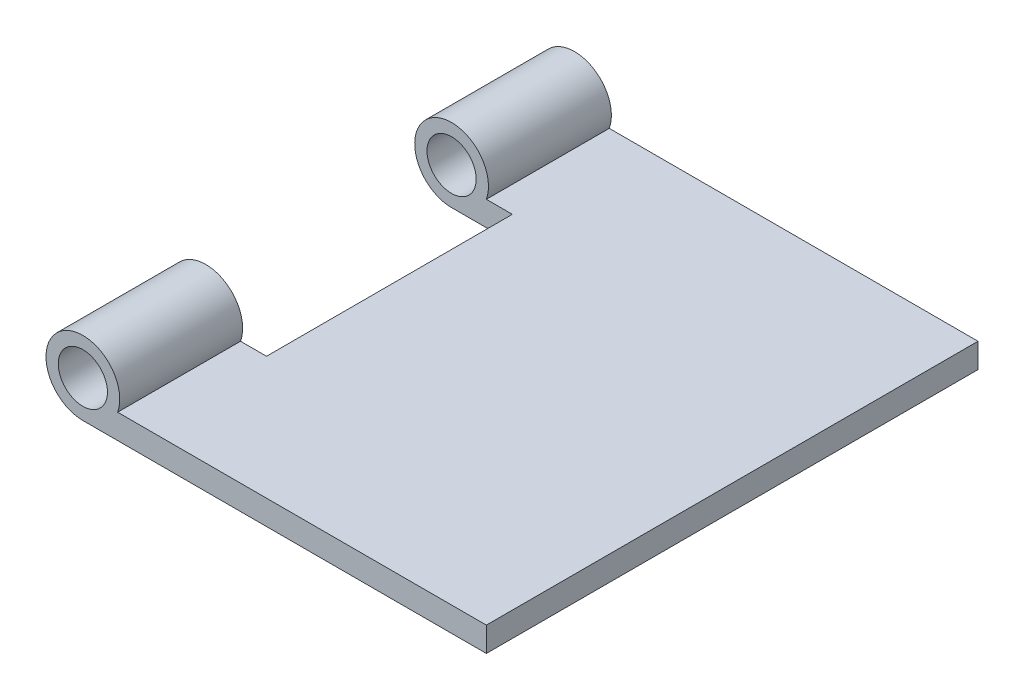
SolidWorks part; units mm, degrees
ref_plane "Спереди" through (0, 0, 0) normal (0, 0, 1) x (1, 0, 0)
ref_plane "Сверху" through (0, 0, 0) normal (0, 1, 0) x (1, 0, 0)
ref_plane "Справа" through (0, 0, 0) normal (1, 0, 0) x (0, 0, -1)
sketch "Эскиз1" plane through (0, 0, 0) normal (0, 0, 1) x (1, 0, 0)
  line L1 (2.8284, -1) -> (32.8284, -1)
  line L3 (0, -3) -> (32.8284, -3)
  line L4 (32.8284, -1) -> (32.8284, -3)
  arc A0 (2.8284, -1) -> (0, -3) centre (0, 0) ccw
  circle A1 centre (0, 0) radius 2
extrude "Вытянуть1" add sketch "Эскиз1" along normal blind 40
sketch "Эскиз2" plane through (0, 0, 0) normal (0, 1, 0) x (1, 0, 0)
  line L0 (32.8284, 0) -> (2.8284, 0) construction
  line L1 (-5.8336, -10) -> (4.943, -10)
  line L2 (-5.8336, -10) -> (-5.8336, -30)
  line L4 (4.943, -10) -> (4.943, -30)
  line L7 (-5.8336, -30) -> (4.943, -30)
  line L9 (32.8284, -40) -> (2.8284, -40) construction
  dimension "D1" = 10
  dimension "D2" = 10
extrude "Вытянуть2" cut sketch "Эскиз2" against normal mid plane 40
